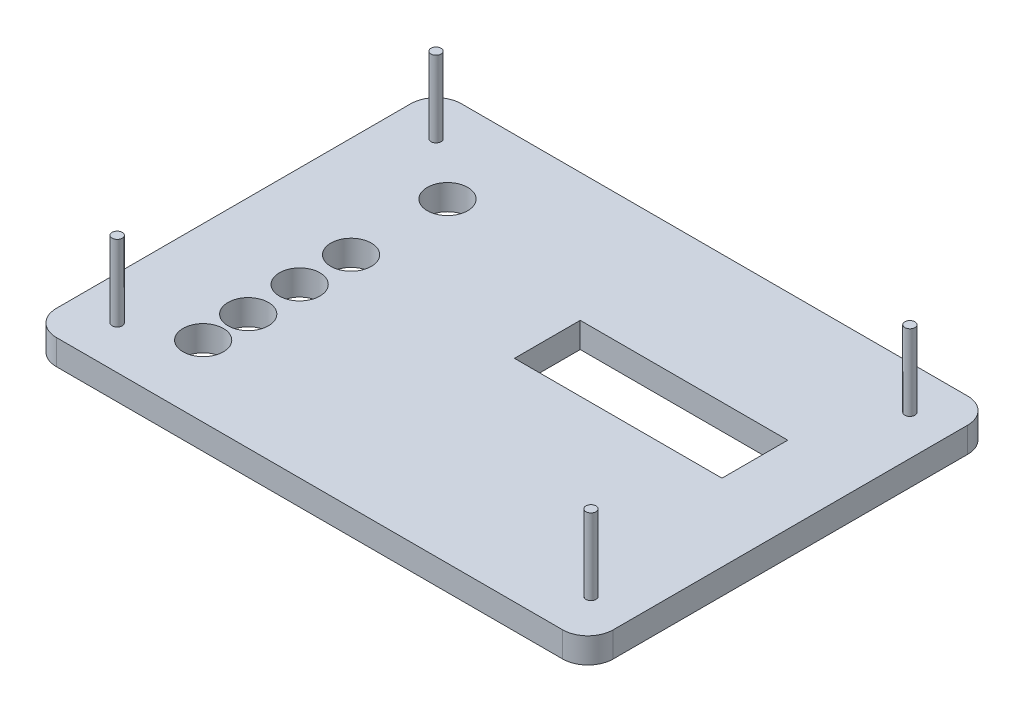
SolidWorks part; units mm, degrees
ref_plane "Front Plane" through (0, 0, 0) normal (0, 0, 1) x (1, 0, 0)
ref_plane "Top Plane" through (0, 0, 0) normal (0, 1, 0) x (1, 0, 0)
ref_plane "Right Plane" through (0, 0, 0) normal (1, 0, 0) x (0, 0, -1)
sketch "Sketch1" plane through (0, 0, 0) normal (0, 1, 0) x (1, 0, 0)
  line L0 (0, 40) -> (0, -40) construction
  line L1 (-55, -40) -> (55, -40)
  line L2 (-55, -40) -> (-55, 40)
  line L3 (-55, 40) -> (55, 40)
  line L4 (55, -40) -> (55, 40)
  line L5 (-55, -40) -> (55, 40) construction
  line L6 (-55, 40) -> (55, -40) construction
  line L7 (-55, 0) -> (55, 0) construction
  circle A1 centre (-35.06, 22.32) radius 4
  circle A2 centre (-35.06, 3.27) radius 4
  circle A3 centre (-35.06, -6.89) radius 4
  circle A4 centre (-35.06, -17.05) radius 4
  circle A5 centre (-35.06, -25.95) radius 4
  point P0 (0, 0)
  dimension "D3" = 8
  dimension "D4" = 17.68
  dimension "D5" = 8
  dimension "D7" = 10.16
  dimension "D8" = 10.16
  dimension "D9" = 8.9
  dimension "D10" = 19.94
  dimension "D1" = 110
  dimension "D2" = 80
  dimension "D6" = 19.05
extrude "Boss-Extrude1" add sketch "Sketch1" along normal blind 5
sketch "Sketch2" plane through (0, 5, 0) normal (0, 1, 0) x (1, 0, 0)
  line L0 (55, -40) -> (55, 40) construction
  line L1 (55, 40) -> (-55, 40) construction
  line L2 (0, 120) -> (0, -40)
  line L3 (-55, -40) -> (55, -40) construction
  line L4 (-55, 0) -> (55, 0) construction
  line L5 (-55, 40) -> (-55, -40) construction
  circle A0 centre (47.1, 31.5) radius 1
  circle A1 centre (47.1, -31.5) radius 1
  circle A2 centre (-46.5, 31.5) radius 1
  circle A3 centre (-46.5, -31.5) radius 1
  point P13 (0, 40)
  dimension "D3" = 2
  dimension "D4" = 2
  dimension "D1" = 7.9
  dimension "D2" = 8.5
  dimension "D5" = 8.5
  dimension "D6" = 8.5
extrude "Boss-Extrude2" add sketch "Sketch2" along normal blind 15 contours A2 | A0 | A1 | A3
fillet "Fillet1" radius 5 4 edges at (-55, 2.5, 40) (55, 2.5, 40) (55, 2.5, -40) (-55, 2.5, -40)
sketch "Sketch3" plane through (0, 0, 0) normal (0, -1, 0) x (1, 0, 0)
  line L1 (39.8, -14.68) -> (-1.2, -14.68)
  line L2 (39.8, -14.68) -> (39.8, -1.68)
  line L3 (39.8, -1.68) -> (-1.2, -1.68)
  line L4 (-1.2, -14.68) -> (-1.2, -1.68)
  line L5 (39.8, -14.68) -> (-1.2, -1.68) construction
  line L6 (39.8, -1.68) -> (-1.2, -14.68) construction
  line L7 (55, 35) -> (55, -35) construction
  line L8 (50, -40) -> (-50, -40) construction
  point P0 (19.3, -8.18)
  point P5 (11.8173, -18.1027)
  point P7 (49.7, -19.3182)
  dimension "D1" = 41
  dimension "D2" = 13
  dimension "D3" = 15.2
  dimension "D4" = 25.32
extrude "Cut-Extrude2" cut sketch "Sketch3" against normal blind 5
